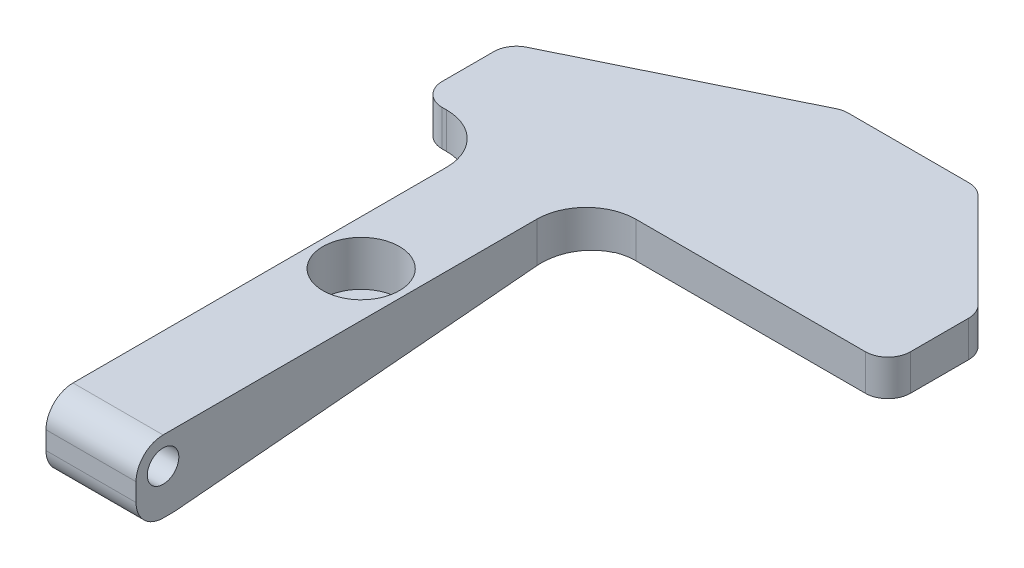
SolidWorks part; units mm, degrees
material "ABS"
ref_plane "Front Plane" through (0, 0, 0) normal (0, 0, 1) x (1, 0, 0)
ref_plane "Top Plane" through (0, 0, 0) normal (0, 1, 0) x (1, 0, 0)
ref_plane "Right Plane" through (0, 0, 0) normal (1, 0, 0) x (0, 0, -1)
sketch "Sketch1" plane through (0, 0, 0) normal (1, 0, 0) x (0, 0, -1)
  line L0 (-3, 0) -> (-3, -5.3744)
  line L4 (0, 3) -> (47, 3)
  line L6 (-3, -5.3744) -> (47, -1)
  line L8 (-3, 0) -> (0, 0) construction
  line L9 (47, 3) -> (47, -1)
  line L10 (-3, -5) -> (1.2798, -5)
  circle A0 centre (0, 0) radius 1.75
  arc A1 (0, 3) -> (-3, 0) centre (0, 0) ccw
  point P5 (0, 0)
  point P7 (47, -0.9629)
  point P13 (0, 0)
  dimension "D1" = 3.5
  dimension "D2" = 3
  dimension "D3" = 4
  dimension "D4" = 5
  dimension "D5" = 50
  dimension "D7" = 8
extrude "Boss-Extrude1" add sketch "Sketch1" along normal mid plane 17
fillet "Fillet1" radius 3 1 edges at (0, -5, 3)
sketch "Sketch2" plane through (0, 3, 0) normal (0, 1, 0) x (1, 0, 0)
  line L0 (-8.5, 42) -> (-4, 42) construction
  line L1 (-8.5, 0) -> (-8.5, 47) construction
  line L2 (-4, 42) -> (4, 42) construction
  line L3 (4, 42) -> (8.5, 42) construction
  line L4 (8.5, 0) -> (8.5, 47) construction
  line L5 (8.5, 47) -> (-8.5, 47) construction
  line L7 (0.75, 40.1236) -> (4, 38.2472)
  line L8 (4, 38.2472) -> (7.25, 40.1236)
  line L9 (7.25, 40.1236) -> (7.25, 43.8764)
  line L10 (7.25, 43.8764) -> (4, 45.7528)
  line L11 (4, 45.7528) -> (0.75, 43.8764)
  line L12 (0.75, 43.8764) -> (0.75, 40.1236)
  line L13 (-0.75, 43.8764) -> (-4, 45.7528)
  line L14 (-4, 45.7528) -> (-7.25, 43.8764)
  line L15 (-7.25, 43.8764) -> (-7.25, 40.1236)
  line L16 (-7.25, 40.1236) -> (-4, 38.2472)
  line L17 (-4, 38.2472) -> (-0.75, 40.1236)
  line L18 (-0.75, 40.1236) -> (-0.75, 43.8764)
  circle A0 centre (-4, 42) radius 1.75
  circle A1 centre (4, 42) radius 1.75
  circle A2 centre (4, 42) radius 3.25 construction
  circle A3 centre (-4, 42) radius 3.25 construction
  dimension "D1" = 3.5
  dimension "D2" = 8
  dimension "7.5" = 5
  dimension "D4" = 6.5
extrude "Cut-Extrude2" [suppressed] cut sketch "Sketch2" against normal blind 2 contours L11 L12 L7 L8 L9 L10 A1 | L17 L18 L13 L14 L15 L16 A0
sketch "Sketch3" plane through (0, 3, 0) normal (0, 1, 0) x (1, 0, 0)
  line L0 (0, 27) -> (0, 0) construction
  line L1 (0, 27) -> (0, 38) construction
  circle A0 centre (0, 27) radius 4.25
  dimension "D3" = 8.5
  dimension "D1" = 38
  dimension "D2" = 11
extrude "Cut-Extrude3" cut sketch "Sketch3" against normal blind 5
sketch "Sketch4" plane through (0, 3, 0) normal (0, 1, 0) x (1, 0, 0)
  line L0 (0, 0) -> (0, 47) construction
  line L1 (8.5, 47) -> (-8.5, 47) construction
  line L2 (8.5, -3) -> (-8.5, -3) construction
  line L3 (5, -3) -> (-5, -3) construction
  line L4 (5, -3) -> (5, 36) construction
  line L5 (5, 36) -> (-5, 36) construction
  line L6 (-5, -3) -> (-5, 36) construction
  line L7 (0, 36) -> (0, -3) construction
  line L8 (5, 16.5) -> (-5, 16.5) construction
  line L9 (-8.5, -3) -> (-5, -3)
  line L10 (-5, -3) -> (-5, 32.6)
  line L11 (-8.4, 36) -> (-8.5, 36)
  line L12 (-8.5, 36) -> (-8.5, -3)
  line L14 (8.4, 36) -> (8.5, 36)
  line L15 (5, -3) -> (5, 32.6)
  line L16 (8.5, -3) -> (5, -3)
  line L17 (8.5, 36) -> (8.5, -3)
  arc A0 (8.4, 36) -> (5, 32.6) centre (8.4, 32.6) ccw
  arc A1 (-5, 32.6) -> (-8.4, 36) centre (-8.4, 32.6) ccw
  point P5 (0, 16.5)
  dimension "D4" = 3.4
  dimension "D1" = 10
  dimension "D2" = 11
  dimension "D3" = 3.5
extrude "Cut-Extrude4" cut sketch "Sketch4" against normal up to next
sketch "Sketch5" plane through (0, 3, 0) normal (0, 1, 0) x (1, 0, 0)
  line L0 (-8.5, 47) -> (-11, 47)
  line L1 (8.5, 47) -> (-8.5, 47) construction
  line L2 (-8.5, 36) -> (-8.5, 47) construction
  line L3 (-13.5, 49.5) -> (-13.5, 55.2378)
  line L4 (-12.0959, 57.4848) -> (10.9949, 68.747)
  line L5 (12.0909, 69) -> (25.4645, 69)
  line L6 (27.2322, 68.2678) -> (37.7678, 57.7322)
  line L7 (38.5, 55.9645) -> (38.5, 49.5)
  line L8 (36, 47) -> (8.5, 47)
  line L9 (8.5, 36) -> (8.5, 47) construction
  line L10 (-8.5, 47) -> (-8.5, 45)
  line L11 (8.5, 47) -> (8.5, 45)
  arc A0 (38.5, 49.5) -> (36, 47) centre (36, 49.5) cw
  arc A1 (37.7678, 57.7322) -> (38.5, 55.9645) centre (36, 55.9645) cw
  arc A2 (25.4645, 69) -> (27.2322, 68.2678) centre (25.4645, 66.5) cw
  arc A3 (10.9949, 68.747) -> (12.0909, 69) centre (12.0909, 66.5) cw
  arc A4 (-13.5, 55.2378) -> (-12.0959, 57.4848) centre (-11, 55.2378) cw
  arc A5 (-11, 47) -> (-13.5, 49.5) centre (-11, 49.5) cw
  arc A6 (-8.5, 45) -> (-10.5, 47) centre (-10.5, 45) ccw
  arc A7 (10.5, 47) -> (8.5, 45) centre (10.5, 45) ccw
  point P2 (8.5, 45)
  point P10 (8.5, 45)
  point P24 (38.5, 47)
  point P27 (38.5, 57)
  point P34 (-13.5, 56.8)
  point P37 (-13.5, 47)
  line M13 (8.5, 36) -> (8.5, 47)
  line M14 (8.5, 47) -> (-8.5, 47)
  line M15 (-8.5, 47) -> (-8.5, 36)
  dimension "D8" = 2.5
  dimension "D9" = 4
  dimension "D1" = 116
  dimension "D2" = 22
  dimension "D3" = 30
  dimension "D4" = 5
  dimension "D5" = 9.8
  dimension "D6" = 10
  dimension "D7" = 135
extrude "Boss-Extrude2" add sketch "Sketch5" against normal blind 4 contours A5 L0 L8 A0 L7 A1 L6 A2 L5 A3 L4 A4 L3 M14 | A7 L8 M13 | A6 L0 M15
sketch "Sketch6" plane through (0, 3, 0) normal (0, 1, 0) x (1, 0, 0)
  line L0 (5, 32.6) -> (5, 41.5)
  line L1 (5, 32.6) -> (10.5, 32.6)
  line L2 (10.5, 32.6) -> (10.5, 47)
  line L3 (-5, 16.3) -> (5, 16.3) construction
  line L6 (-5, 0) -> (-5, 32.6) construction
  line L7 (5, 32.6) -> (5, 0) construction
  line L8 (0, 16.3) -> (0, 60.8249) construction
  line L9 (-5, 32.6) -> (-10.5, 32.6)
  line L10 (-5, 32.6) -> (-5, 41.5)
  line L11 (-10.5, 32.6) -> (-10.5, 47)
  arc A0 (10.5, 47) -> (5, 41.5) centre (10.5, 41.5) ccw
  arc A1 (-10.5, 47) -> (-5, 41.5) centre (-10.5, 41.5) cw
  dimension "D1" = 5.5
extrude "Cut-Extrude5" cut sketch "Sketch6" against normal up to next
